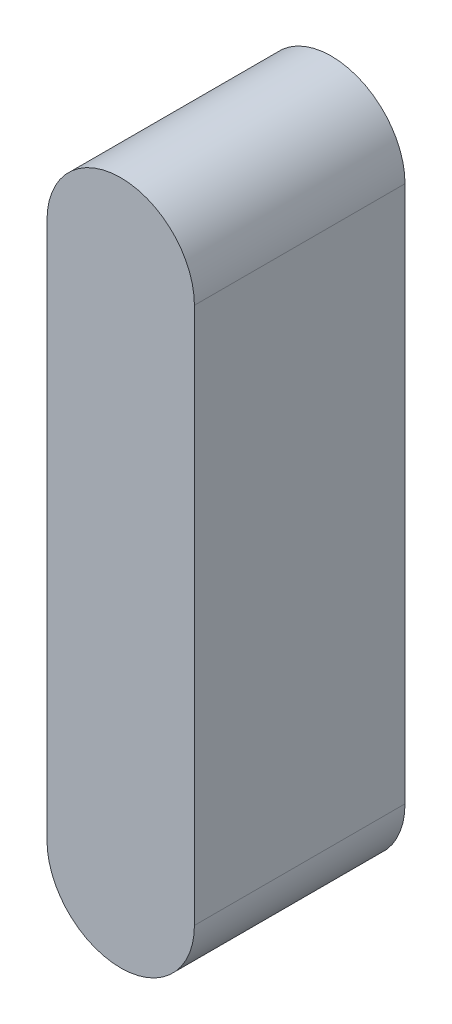
SolidWorks part; units mm, degrees
ref_plane "Front Plane" through (0, 0, 0) normal (0, 0, 1) x (1, 0, 0)
ref_plane "Top Plane" through (0, 0, 0) normal (0, 1, 0) x (1, 0, 0)
ref_plane "Right Plane" through (0, 0, 0) normal (1, 0, 0) x (0, 0, -1)
sketch "Sketch1" plane through (0, 0, 0) normal (0, 0, 1) x (1, 0, 0)
  line L0 (0, -5.1) -> (0, 5.1) construction
  line L1 (-1.4, -5.1) -> (-1.4, 5.1)
  line L2 (1.4, -5.1) -> (1.4, 5.1)
  line L3 (0, 6.5) -> (0, -6.5)
  arc A0 (-1.4, -5.1) -> (1.4, -5.1) centre (0, -5.1) ccw
  arc A1 (1.4, 5.1) -> (-1.4, 5.1) centre (0, 5.1) ccw
  point P2 (0, 0)
  dimension "D1" = 13
  dimension "D2" = 2.8
extrude "Boss-Extrude1" add sketch "Sketch1" along normal blind 4 contours L2 A1 L3 A0 | L3 A1 L1 A0
